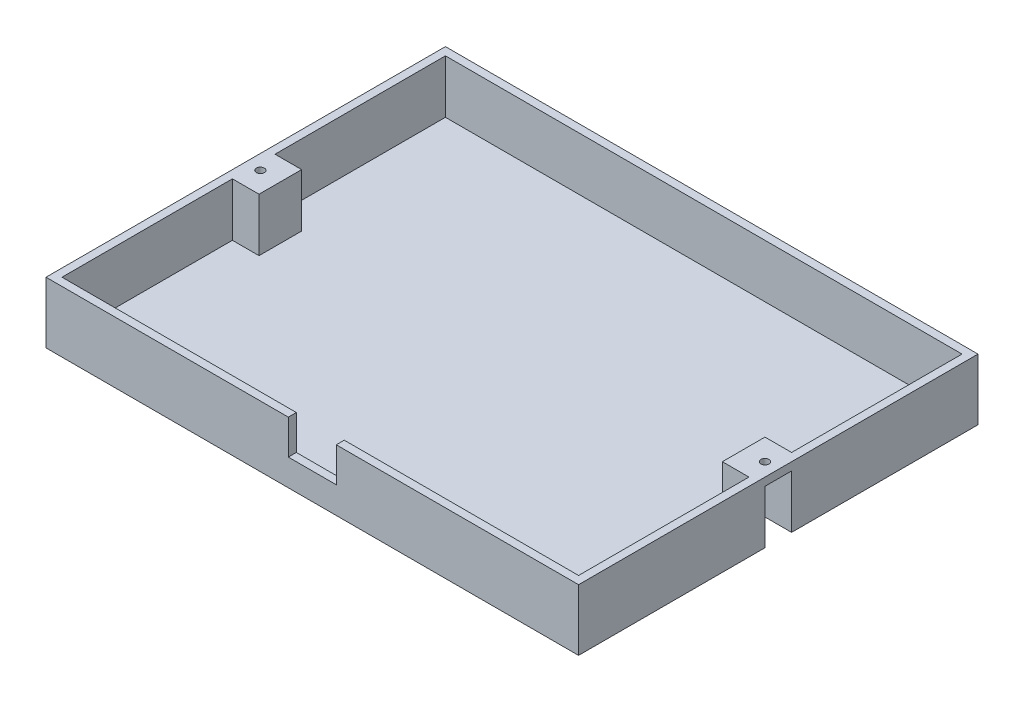
SolidWorks part; units mm, degrees
ref_plane "Front Plane" through (0, 0, 0) normal (0, 0, 1) x (1, 0, 0)
ref_plane "Top Plane" through (0, 0, 0) normal (0, 1, 0) x (1, 0, 0)
ref_plane "Right Plane" through (0, 0, 0) normal (1, 0, 0) x (0, 0, -1)
sketch "Sketch1" plane through (0, 0, 0) normal (0, 1, 0) x (1, 0, 0)
  line L1 (-100, 75) -> (100, 75)
  line L2 (-100, 75) -> (-100, -75)
  line L3 (-100, -75) -> (100, -75)
  line L4 (100, 75) -> (100, -75)
  line L5 (-100, 75) -> (100, -75) construction
  line L6 (-100, -75) -> (100, 75) construction
  point P0 (0, 0)
  dimension "D1" = 200
  dimension "D2" = 150
extrude "Boss-Extrude1" add sketch "Sketch1" along normal blind 3
sketch "Sketch2" plane through (0, 3, 0) normal (0, 1, 0) x (1, 0, 0)
  line L0 (0, -1.65) -> (0, 1.65) construction
  line L1 (100, -5) -> (90, -5)
  line L2 (90, 5) -> (90, -5)
  line L3 (100, 5) -> (90, 5)
  line L4 (100, 5) -> (100, 75)
  line L5 (-100, -5) -> (-100, -75)
  line L6 (-100, 5) -> (-90, 5)
  line L8 (100, -75) -> (100, 75)
  line L9 (100, 75) -> (-100, 75)
  line L10 (-100, 75) -> (-100, -75)
  line L11 (-100, -75) -> (100, -75)
  line L12 (100, -75) -> (100, -5)
  line L13 (100, 75) -> (-100, 75)
  line L14 (-100, 75) -> (-100, 5)
  line L15 (-100, -75) -> (100, -75)
  line L16 (-100, -5) -> (-90, -5)
  line L17 (-90, 5) -> (-90, -5)
  line L19 (97, -8) -> (87, -8)
  line L20 (87, 8) -> (87, -8)
  line L21 (97, 8) -> (87, 8)
  line L22 (97, 8) -> (97, 72)
  line L23 (97, 72) -> (-97, 72)
  line L24 (-97, 72) -> (-97, 8)
  line L25 (-97, 8) -> (-87, 8)
  line L26 (-87, 8) -> (-87, -8)
  line L27 (-97, -8) -> (-87, -8)
  line L28 (-97, -8) -> (-97, -72)
  line L29 (-97, -72) -> (97, -72)
  line L30 (97, -72) -> (97, -8)
  point P6 (-116.8014, -12.205)
  dimension "D2" = 10
  dimension "D3" = 3
  dimension "D4" = 10
  dimension "D1" = 0
extrude "Boss-Extrude2" add sketch "Sketch2" along normal blind 20
sketch "Sketch3" plane through (0, 23, 0) normal (0, 1, 0) x (1, 0, 0)
  line L1 (-100, 5) -> (-90, 5)
  line L2 (-100, 5) -> (-100, -5)
  line L3 (-100, -5) -> (-90, -5)
  line L4 (-90, 5) -> (-90, -5)
extrude "Boss-Extrude3" add sketch "Sketch3" against normal blind 3
sketch "Sketch4" plane through (0, 3, 0) normal (0, 1, 0) x (1, 0, 0)
  line L8 (-100, -5) -> (-90, -5)
  line L9 (-90, -5) -> (-90, 5)
  line L10 (-90, 5) -> (-100, 5)
  line L11 (-100, 5) -> (-100, -5)
  line L12 (-100, -5) -> (-90, -5)
  line L13 (-90, -5) -> (-90, 5)
  line L14 (-90, 5) -> (-100, 5)
  line L15 (-100, 5) -> (-100, -5)
  dimension "D1" = 0
extrude "Cut-Extrude1" cut sketch "Sketch4" against normal through all
sketch "Sketch5" plane through (0, 23, 0) normal (0, 1, 0) x (1, 0, 0)
  line L1 (90, 5) -> (100, 5)
  line L2 (90, 5) -> (90, -5)
  line L3 (90, -5) -> (100, -5)
  line L4 (100, 5) -> (100, -5)
extrude "Boss-Extrude4" add sketch "Sketch5" against normal blind 3
sketch "Sketch6" plane through (0, 3, 0) normal (0, 1, 0) x (1, 0, 0)
  line L8 (100, 5) -> (90, 5)
  line L9 (90, 5) -> (90, -5)
  line L10 (90, -5) -> (100, -5)
  line L11 (100, -5) -> (100, 5)
  line L12 (100, 5) -> (90, 5)
  line L13 (90, 5) -> (90, -5)
  line L14 (90, -5) -> (100, -5)
  line L15 (100, -5) -> (100, 5)
  dimension "D1" = 0
extrude "Cut-Extrude2" cut sketch "Sketch6" against normal blind 3
sketch "Sketch7" plane through (0, 20, 0) normal (0, -1, 0) x (1, 0, 0)
  line L0 (100, 0) -> (90, 0) construction
  line L1 (100, 5) -> (100, -5) construction
  line L2 (90, -5) -> (90, 5) construction
  circle A0 centre (95, 0) radius 1.5
  dimension "D1" = 3
  dimension "D2" = 5
extrude "Cut-Extrude3" cut sketch "Sketch7" against normal through all
sketch "Sketch8" plane through (0, 20, 0) normal (0, -1, 0) x (1, 0, 0)
  line L0 (-100, 0) -> (-90, 0) construction
  line L1 (-100, -5) -> (-100, 5) construction
  line L2 (-90, 5) -> (-90, -5) construction
  circle A0 centre (-94.5, 0) radius 1.5
  dimension "D1" = 3
  dimension "D2" = 5.5
extrude "Cut-Extrude4" cut sketch "Sketch8" against normal through all
sketch "Sketch10" plane through (0, 0, 75) normal (0, 0, 1) x (1, 0, 0)
  line L0 (0, 23) -> (0, 0) construction
  line L1 (-100, 23) -> (100, 23) construction
  line L2 (-100, 0) -> (100, 0) construction
  line L4 (-9, 23) -> (9, 23)
  line L5 (-9, 23) -> (-9, 10)
  line L6 (-9, 10) -> (9, 10)
  line L7 (9, 23) -> (9, 10)
  point P10 (9, 16.5)
  dimension "D1" = 9
  dimension "D2" = 18
  dimension "D3" = 13
extrude "Cut-Extrude5" cut sketch "Sketch10" against normal blind 3
